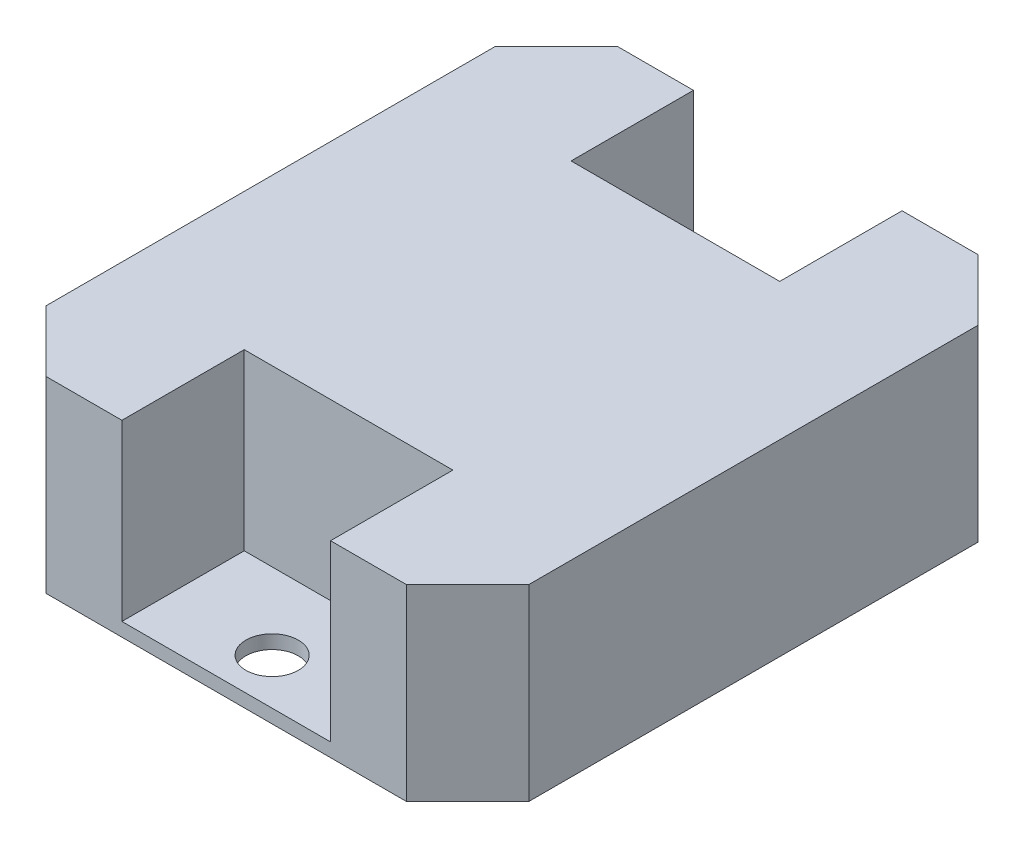
SolidWorks part; units mm, degrees
ref_plane "Front Plane" through (0, 0, 0) normal (0, 0, 1) x (1, 0, 0)
ref_plane "Top Plane" through (0, 0, 0) normal (0, 1, 0) x (1, 0, 0)
ref_plane "Right Plane" through (0, 0, 0) normal (1, 0, 0) x (0, 0, -1)
sketch "Sketch1" plane through (0, 0, 0) normal (0, 1, 0) x (1, 0, 0)
  line B0 (-28.0654, 26.1129) -> (-20.953, 33.2245)
  line B1 (-20.957, -33.2219) -> (20.953, -33.2245)
  line B2 (-28.0686, -26.1095) -> (-28.0654, 26.1129)
  line B3 (-20.953, 33.2245) -> (20.957, 33.2219)
  line B4 (28.0654, -26.1129) -> (28.0686, 26.1095)
  line B5 (-28.065, 33.2249) -> (28.065, -33.2249) construction
  line B6 (20.957, 33.2219) -> (28.0686, 26.1095)
  line B7 (20.953, -33.2245) -> (28.0654, -26.1129)
  line B8 (-28.0686, -26.1095) -> (-20.957, -33.2219)
  circle B9 centre (0.0017, 27.8892) radius 3.048
  circle B10 centre (-0.0017, -27.8892) radius 3.048
sketch_block_instance "12-5v Converter-1"
sketch_block "12-5v Converter" parameters "D3"=7.7092, "D4"=6.2489, "D5"=7.7092, "D1"=56.134, "D2"=66.4464
extrude "Boss-Extrude1" add sketch "Sketch1" along normal blind 21.844
sketch "Sketch2" plane through (0, 21.844, 0) normal (0, 1, 0) x (1, 0, 0)
  line L1 (-12.1305, -33.4772) -> (12.1265, -33.4772)
  line L2 (-12.1305, -33.4772) -> (-12.1305, -18.9992)
  line L3 (-12.1305, -18.9992) -> (12.1265, -18.9992)
  line L4 (12.1265, -33.4772) -> (12.1265, -18.9992)
  line L5 (12.1265, 18.9992) -> (-12.1305, 18.9992)
  line L6 (12.1265, 18.9992) -> (12.1265, 33.4772)
  line L7 (12.1265, 33.4772) -> (-12.1305, 33.4772)
  line L8 (-12.1305, 18.9992) -> (-12.1305, 33.4772)
  line L9 (20.957, 33.2219) -> (-20.953, 33.2245) construction
  line L10 (-20.957, -33.2219) -> (20.953, -33.2245) construction
  point P8 (-0.002, -33.4772)
  point P9 (0.002, 33.2232)
  point P10 (-0.002, 33.4772)
  point P12 (-0.002, -33.2232)
  dimension "D1" = 24.257
  dimension "D2" = 14.478
  dimension "D3" = 0.254
  dimension "D4" = 0.254
extrude "Cut-Extrude1" cut sketch "Sketch2" against normal offset from surface (20.2565 mm away) 1.5875 up to face at (0.0017, 0, -24.8412)
